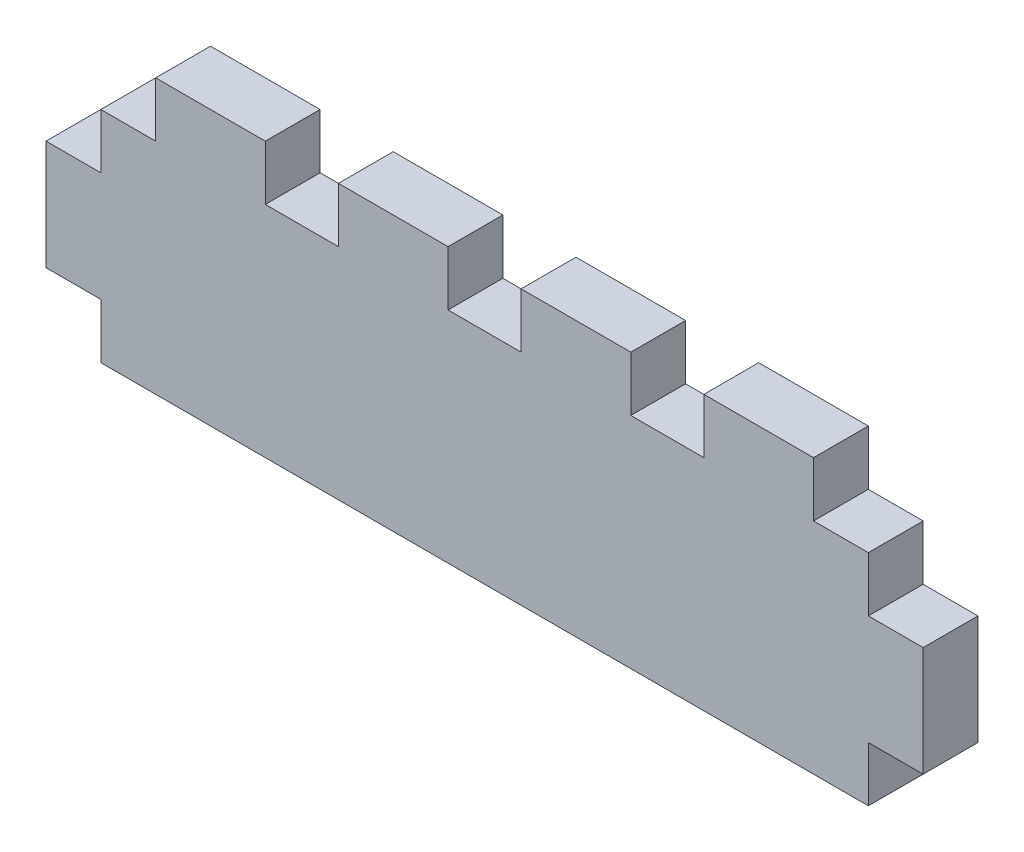
SolidWorks part; units mm, degrees
material "Balsa"
ref_plane "Front Plane" through (0, 0, 0) normal (0, 0, 1) x (1, 0, 0)
ref_plane "Top Plane" through (0, 0, 0) normal (0, 1, 0) x (1, 0, 0)
ref_plane "Right Plane" through (0, 0, 0) normal (1, 0, 0) x (0, 0, -1)
sketch "Sketch1" plane through (0, 0, 0) normal (0, 0, 1) x (1, 0, 0)
  line L1 (0, 0) -> (-177.8, 0)
  line L2 (0, 0) -> (0, 50.8)
  line L3 (0, 50.8) -> (-177.8, 50.8)
  line L4 (-177.8, 0) -> (-177.8, 50.8)
  dimension "D1" = 177.8
  dimension "D2" = 50.8
extrude "Boss-Extrude1" add sketch "Sketch1" along normal blind 12.7
sketch "Sketch2" plane through (0, 0, 12.7) normal (0, 0, 1) x (1, 0, 0)
  line L0 (0, 50.8) -> (-177.8, 50.8) construction
  line L1 (-165.1, 50.8) -> (-139.7, 50.8)
  line L2 (-165.1, 50.8) -> (-165.1, 63.5)
  line L3 (-165.1, 63.5) -> (-139.7, 63.5)
  line L4 (-139.7, 50.8) -> (-139.7, 63.5)
  line L5 (-177.6329, 63.5) -> (0, 63.5) construction
  line L6 (-122.7667, 63.5) -> (-97.3667, 63.5)
  line L7 (-122.7667, 63.5) -> (-122.7667, 50.8)
  line L8 (-122.7667, 50.8) -> (-97.3667, 50.8)
  line L9 (-97.3667, 63.5) -> (-97.3667, 50.8)
  line L10 (-80.4333, 63.5) -> (-55.0333, 63.5)
  line L11 (-80.4333, 63.5) -> (-80.4333, 50.8)
  line L12 (-80.4333, 50.8) -> (-55.0333, 50.8)
  line L13 (-55.0333, 63.5) -> (-55.0333, 50.8)
  line L14 (-38.1, 63.5) -> (-12.7, 63.5)
  line L15 (-38.1, 63.5) -> (-38.1, 50.8)
  line L16 (-38.1, 50.8) -> (-12.7, 50.8)
  line L17 (-12.7, 63.5) -> (-12.7, 50.8)
  line L18 (-139.7, 50.8) -> (-122.7667, 50.8) construction
  line L20 (-97.3667, 50.8) -> (-80.4333, 50.8) construction
  line L21 (-55.0333, 50.8) -> (-38.1, 50.8) construction
  line L22 (-88.9, 50.8) -> (-88.9, 0) construction
  line L23 (-177.8, 0) -> (0, 0) construction
  line L24 (-177.8, 50.8) -> (-177.8, 0) construction
  line L25 (-177.8, 25.4) -> (0, 25.4) construction
  line L26 (0, 0) -> (0, 50.8) construction
  line L27 (-55.0333, 0) -> (-38.1, 0) construction
  line L28 (-97.3667, 0) -> (-80.4333, 0) construction
  line L30 (-139.7, 0) -> (-122.7667, 0) construction
  line L31 (-12.7, -12.7) -> (-12.7, 0) construction
  line L32 (-38.1, 0) -> (-12.7, 0) construction
  line L33 (-38.1, -12.7) -> (-38.1, 0) construction
  line L34 (-38.1, -12.7) -> (-12.7, -12.7) construction
  line L35 (-55.0333, -12.7) -> (-55.0333, 0) construction
  line L36 (-80.4333, 0) -> (-55.0333, 0) construction
  line L37 (-80.4333, -12.7) -> (-80.4333, 0) construction
  line L38 (-80.4333, -12.7) -> (-55.0333, -12.7) construction
  line L39 (-97.3667, -12.7) -> (-97.3667, 0) construction
  line L40 (-122.7667, 0) -> (-97.3667, 0) construction
  line L41 (-122.7667, -12.7) -> (-122.7667, 0) construction
  line L42 (-122.7667, -12.7) -> (-97.3667, -12.7) construction
  line L43 (-139.7, 0) -> (-139.7, -12.7) construction
  line L44 (-165.1, -12.7) -> (-139.7, -12.7) construction
  line L45 (-165.1, 0) -> (-165.1, -12.7) construction
  line L46 (-165.1, 0) -> (-139.7, 0) construction
  line L47 (0, 38.1) -> (0, 12.7)
  line L48 (-190.5, 38.1) -> (-177.8, 38.1)
  line L49 (-190.5, 38.1) -> (-190.5, 12.7)
  line L50 (-190.5, 12.7) -> (-177.8, 12.7)
  line L51 (-177.8, 38.1) -> (-177.8, 12.7)
  line L52 (12.7, 12.7) -> (0, 12.7)
  line L53 (12.7, 38.1) -> (12.7, 12.7)
  line L54 (12.7, 38.1) -> (0, 38.1)
  dimension "D1" = 25.4
  dimension "D2" = 12.7
  dimension "D3" = 12.7
  dimension "D4" = 25.4
  dimension "D5" = 12.7
extrude "Boss-Extrude2" add sketch "Sketch2" against normal through all
